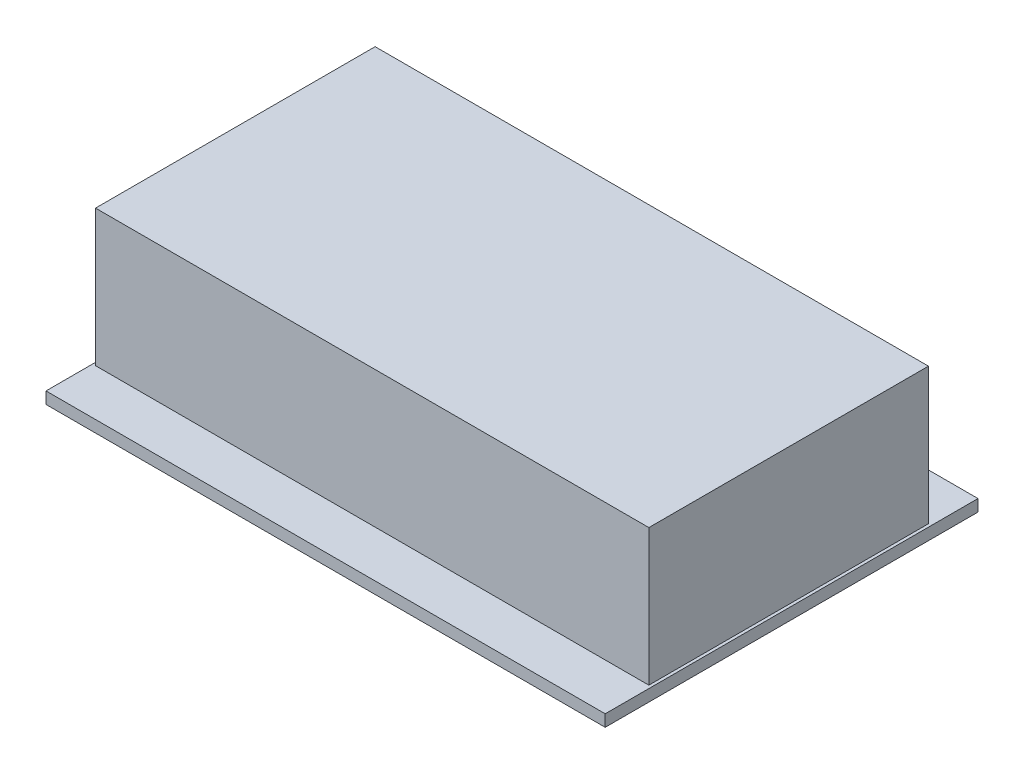
SolidWorks part; units mm, degrees
ref_plane "Front Plane" through (0, 0, 0) normal (0, 0, 1) x (1, 0, 0)
ref_plane "Top Plane" through (0, 0, 0) normal (0, 1, 0) x (1, 0, 0)
ref_plane "Right Plane" through (0, 0, 0) normal (1, 0, 0) x (0, 0, -1)
sketch "Sketch1" plane through (0, 0, 0) normal (0, 1, 0) x (1, 0, 0)
  line L1 (-38.1, -25.4) -> (38.1, -25.4)
  line L2 (-38.1, -25.4) -> (-38.1, 25.4)
  line L3 (-38.1, 25.4) -> (38.1, 25.4)
  line L4 (38.1, -25.4) -> (38.1, 25.4)
  line L5 (-38.1, -25.4) -> (38.1, 25.4) construction
  line L6 (-38.1, 25.4) -> (38.1, -25.4) construction
  point P0 (0, 0)
  dimension "D1" = 76.2
  dimension "D2" = 50.8
extrude "Boss-Extrude1" add sketch "Sketch1" along normal blind 1.6 contours L2 L3 L4 L1
sketch "Sketch2" plane through (0, 1.6, 0) normal (0, 1, 0) x (1, 0, 0)
  line L0 (-37.7, -19.05) -> (-37.7, 19.05)
  line L1 (-37.7, -19.05) -> (37.7, -19.05)
  line L2 (-37.7, 19.05) -> (37.7, 19.05)
  line L3 (37.7, -19.05) -> (37.7, 19.05)
  line L4 (-37.7, -19.05) -> (37.7, 19.05) construction
  line L5 (-37.7, 19.05) -> (37.7, -19.05) construction
  point P1 (0, 0)
  dimension "D1" = 75.4
  dimension "D2" = 38.1
extrude "Boss-Extrude2" add sketch "Sketch2" along normal blind 18.6
